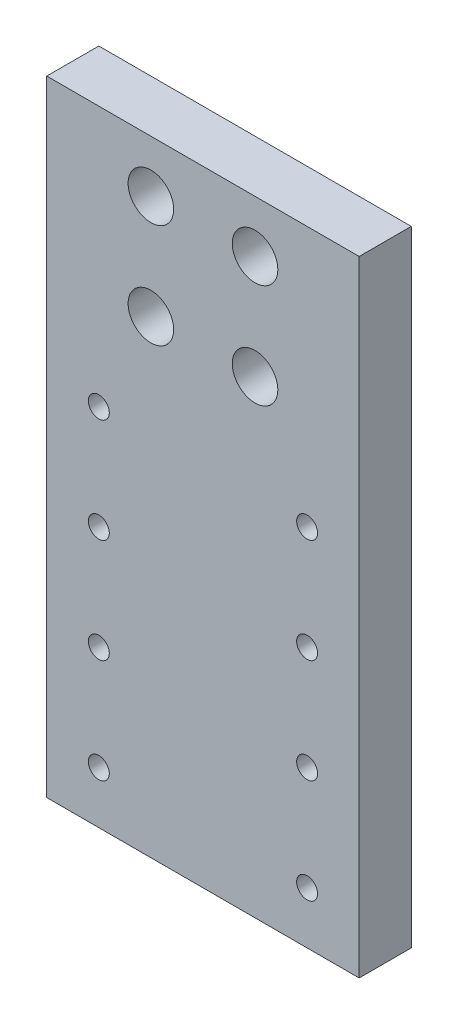
SolidWorks part; units mm, degrees
ref_plane "Front Plane" through (0, 0, 0) normal (0, 0, 1) x (1, 0, 0)
ref_plane "Top Plane" through (0, 0, 0) normal (0, 1, 0) x (1, 0, 0)
ref_plane "Right Plane" through (0, 0, 0) normal (1, 0, 0) x (0, 0, -1)
sketch "Sketch1" plane through (0, 0, 0) normal (0, 0, 1) x (1, 0, 0)
  line L0 (38.1, 0) -> (-38.1, 0) construction
  line L1 (-38.1, -127) -> (38.1, -127)
  line L2 (-38.1, -127) -> (-38.1, 25.4)
  line L3 (-38.1, 25.4) -> (38.1, 25.4)
  line L4 (38.1, -127) -> (38.1, 25.4)
  point P0 (0, 0)
  dimension "D1" = 76.2
  dimension "D2" = 152.4
  dimension "D3" = 25.4
extrude "Boss-Extrude1" add sketch "Sketch1" along normal blind 12.7
hole_wizard "CBORE for 1/4 Socket Head Cap Screw1" positions "Sketch2" profile "Sketch3" counterbore size "1/4" standard "ANSI Inch" end condition through all
sketch "Sketch2" plane through (0, 0, 12.7) normal (0, 0, 1) x (1, 0, 0)
  line L0 (-12.7, 12.7) -> (12.7, -12.7) construction
  point P0 (-12.7, 12.7)
  point P2 (-12.7, -12.7)
  point P4 (12.7, -12.7)
  point P6 (12.7, 12.7)
  point P13 (0, 0)
  dimension "D1" = 25.4
  dimension "D2" = 25.4
  dimension "D3" = 25.4
sketch "Sketch3" plane through (-12.7, 12.7, 12.7) normal (1, 0, 0) x (0, -1, 0)
  line L0 (0, 0) -> (0, 12.7)
  line L1 (0, 12.7) -> (3.3782, 12.7)
  line L3 (3.3782, 12.7) -> (3.3782, 8.89)
  line L4 (3.3782, 8.89) -> (5.5562, 8.89)
  line L5 (5.5562, 8.89) -> (5.5562, 0)
  line L7 (5.5562, 0) -> (0, 0)
  line L11 (0, -6.35) -> (0, 107.95) construction
  dimension "Thru Hole Dia." = 6.7564
  dimension "Thru Hole Depth" = 12.7
  dimension "C'Bore Dia." = 11.1125
  dimension "C'Bore Depth" = 8.89
hole_wizard "CBORE for #10 Socket Head Cap Screw1" positions "Sketch4" profile "Sketch5" counterbore size "#10" standard "ANSI Inch" end condition through all
sketch "Sketch4" plane through (0, 0, 0) normal (0, 0, -1) x (-1, 0, 0)
  line L2 (-38.1, -127) -> (-38.1, 25.4) construction
  line L3 (38.1, -127) -> (-38.1, -127) construction
  point P46 (-25.4, -114.3)
  point P73 (25.4, -114.3)
  point P74 (25.4, -88.9)
  point P75 (25.4, -63.5)
  point P76 (25.4, -38.1)
  point P77 (-25.4, -88.9)
  point P78 (-25.4, -63.5)
  point P79 (-25.4, -38.1)
  dimension "D1" = 12.7
  dimension "D2" = 12.7
  dimension "D3" = 2
  dimension "D4" = 4
sketch "Sketch5" plane through (25.4, -114.3, 0) normal (1, 0, 0) x (0, 1, 0)
  line L0 (0, 0) -> (0, 12.7)
  line L1 (0, 12.7) -> (2.5527, 12.7)
  line L3 (2.5527, 12.7) -> (2.5527, 7.366)
  line L4 (2.5527, 7.366) -> (4.7625, 7.366)
  line L5 (4.7625, 7.366) -> (4.7625, 0)
  line L7 (4.7625, 0) -> (0, 0)
  line L11 (0, -6.35) -> (0, 107.95) construction
  dimension "Thru Hole Dia." = 5.1054
  dimension "Thru Hole Depth" = 12.7
  dimension "C'Bore Dia." = 9.525
  dimension "C'Bore Depth" = 7.366
